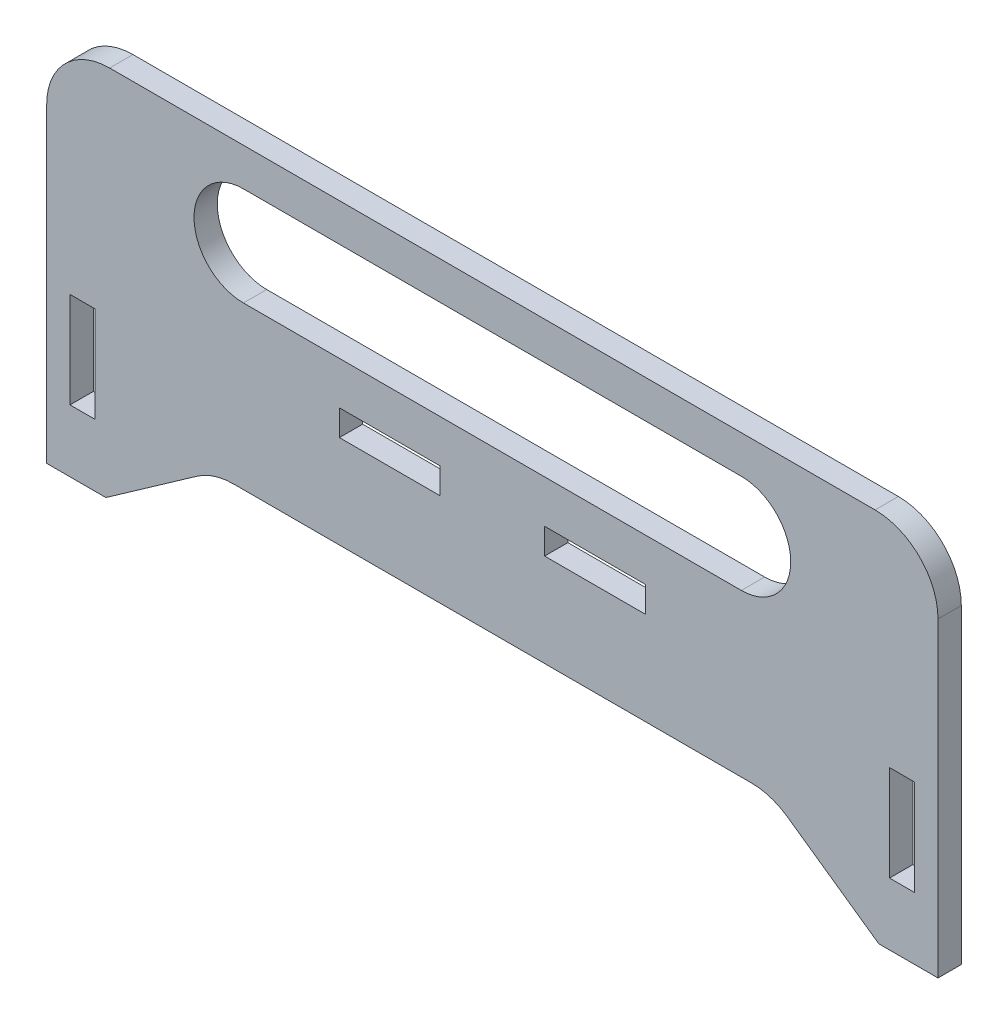
SolidWorks part; units mm, degrees
ref_plane "Front Plane" through (0, 0, 0) normal (0, 0, 1) x (1, 0, 0)
ref_plane "Top Plane" through (0, 0, 0) normal (0, 1, 0) x (1, 0, 0)
ref_plane "Right Plane" through (0, 0, 0) normal (1, 0, 0) x (0, 0, -1)
sketch "Sketch1" plane through (0, 0, 0) normal (0, 0, 1) x (1, 0, 0)
  line L0 (-110.1783, 0) -> (31.4217, 0)
  line L1 (31.4217, 0) -> (31.4217, -59.4)
  line L2 (-110.1783, 0) -> (-110.1783, -59.4)
  line L3 (-110.1783, -59.4) -> (-100.7783, -59.4)
  line L4 (-100.7783, -59.4) -> (-83.6783, -47.3833)
  line L5 (-83.6783, -47.3833) -> (4.9217, -47.3833)
  line L6 (4.9217, -47.3833) -> (22.0217, -59.4)
  line L7 (22.0217, -59.4) -> (31.4217, -59.4)
  line L8 (-39.3783, 0) -> (-39.3783, -94.7126) construction
  line L9 (-110.1783, -13.85) -> (31.4217, -13.85) construction
  line L10 (0.1717, -13.85) -> (-78.9283, -13.85) construction
  line L11 (0.1717, -21.7) -> (-78.9283, -21.7)
  line L12 (0.1717, -6) -> (-78.9283, -6)
  line L13 (-31.0783, -32.6) -> (-31.0783, -28.5)
  line L14 (-47.6783, -32.6) -> (-63.6783, -32.6)
  line L15 (-47.6783, -32.6) -> (-47.6783, -28.5)
  line L16 (-47.6783, -28.5) -> (-63.6783, -28.5)
  line L17 (-63.6783, -32.6) -> (-63.6783, -28.5)
  line L18 (-47.6783, -32.6) -> (-63.6783, -28.5) construction
  line L19 (-47.6783, -28.5) -> (-63.6783, -32.6) construction
  line L20 (-15.0783, -32.6) -> (-15.0783, -28.5)
  line L21 (-31.0783, -32.6) -> (-15.0783, -32.6)
  line L22 (-31.0783, -28.5) -> (-15.0783, -28.5)
  line L23 (27.7217, -49.5) -> (23.7217, -49.5)
  line L24 (-106.4783, -34.3) -> (-102.4783, -34.3)
  line L25 (-106.4783, -34.3) -> (-106.4783, -49.5)
  line L26 (-106.4783, -49.5) -> (-102.4783, -49.5)
  line L27 (-102.4783, -34.3) -> (-102.4783, -49.5)
  line L28 (-106.4783, -34.3) -> (-102.4783, -49.5) construction
  line L29 (-106.4783, -49.5) -> (-102.4783, -34.3) construction
  line L30 (23.7217, -34.3) -> (23.7217, -49.5)
  line L31 (27.7217, -34.3) -> (23.7217, -34.3)
  line L32 (27.7217, -34.3) -> (27.7217, -49.5)
  arc A0 (0.1717, -21.7) -> (0.1717, -6) centre (0.1717, -13.85) ccw
  arc A1 (-78.9283, -6) -> (-78.9283, -21.7) centre (-78.9283, -13.85) ccw
  point P15 (-39.3783, -13.85)
  point P20 (-86.7783, -13.85)
  point P21 (8.0217, -13.85)
  point P22 (-55.6783, -30.55)
  point P31 (-104.4783, -41.9)
  dimension "D1" = 59.4
  dimension "l" = 141.6
  dimension "D2" = 9.4
  dimension "D3" = 88.6
  dimension "D4" = 20.9
  dimension "D5" = 13.85
  dimension "D6" = 15.7
  dimension "D7" = 94.8
  dimension "D8" = 6.8
  dimension "D9" = 46.5
  dimension "D10" = 16
  dimension "D11" = 4.1
  dimension "D12" = 9.9
  dimension "D13" = 3.7
  dimension "D14" = 4
  dimension "D15" = 15.2
extrude "Boss-Extrude2" add sketch "Sketch1" along normal blind 3.7
fillet "Fillet1" radius 10 2 edges at (-110.1783, 0, 1.85) (31.4217, 0, 1.85)
fillet "Fillet2" radius 10 2 edges at (4.9217, -47.3833, 1.85) (-83.6783, -47.3833, 1.85)
